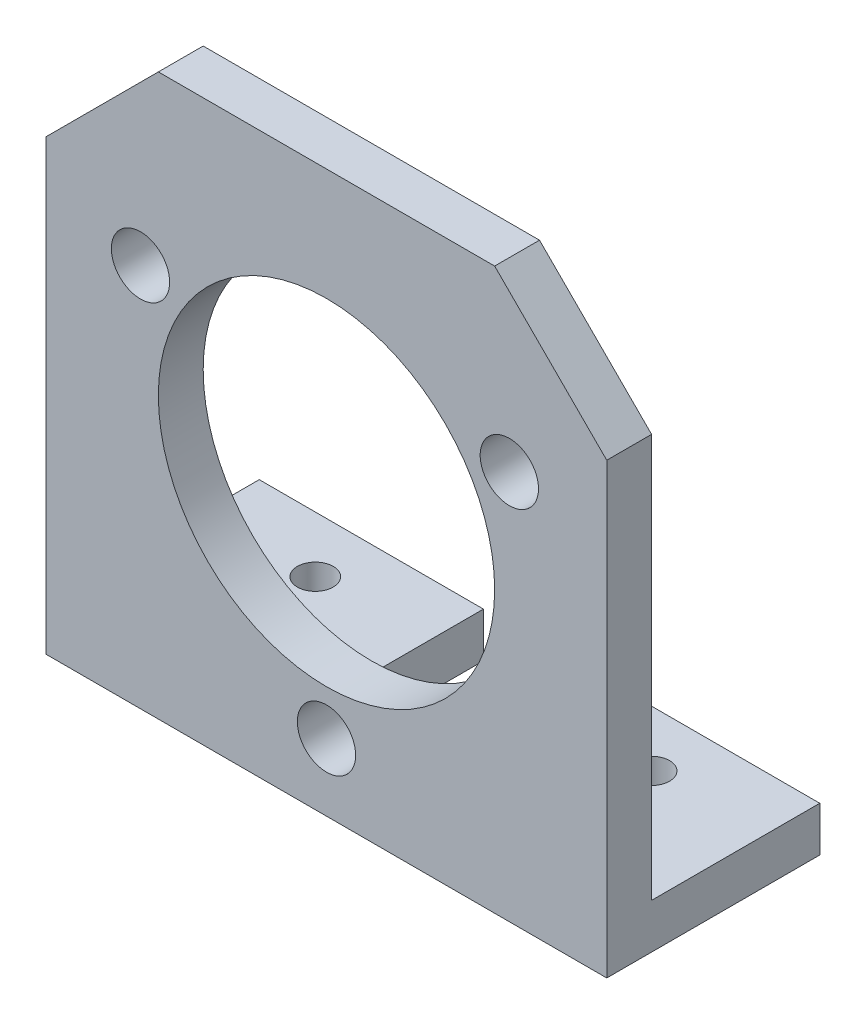
SolidWorks part; units mm, degrees
ref_plane "前视基准面" through (0, 0, 0) normal (0, 0, 1) x (1, 0, 0)
ref_plane "上视基准面" through (0, 0, 0) normal (0, 1, 0) x (1, 0, 0)
ref_plane "右视基准面" through (0, 0, 0) normal (1, 0, 0) x (0, 0, -1)
sketch "草图1" plane through (0, 0, 0) normal (0, 0, 1) x (1, 0, 0)
  line L1 (-25, 0) -> (-25, -25)
  line L2 (25, 0) -> (25, -25)
  line L3 (-25, -25) -> (25, -25)
  line L4 (-25, -21) -> (-5, -21)
  line L5 (5, -21) -> (25, -21)
  line L6 (-5, -21) -> (-5, -25)
  line L7 (5, -21) -> (5, -25)
  line L8 (0, 25) -> (-15, 25)
  line L9 (-25, 15) -> (-25, 0)
  line L10 (-15, 25) -> (-25, 15)
  line L11 (0, 25) -> (15, 25)
  line L12 (25, 15) -> (15, 25)
  line L13 (25, 15) -> (25, 0)
  line L14 (-25, 0) -> (25, 0) construction
  line L15 (0, 28) -> (0, -28) construction
  line L16 (-13.0997, 7.3073) -> (-21.1797, 11.8145) construction
  line L17 (12.8762, 7.6943) -> (20.5365, 12.2718) construction
  circle A0 centre (0, 0) radius 15
  circle A1 centre (-16.593, 9.2559) radius 2.6
  circle A2 centre (16.3099, 9.7462) radius 2.6
  circle A3 centre (0, -19) radius 2.6
  circle A4 centre (0, 0) radius 19 construction
extrude "凸台-拉伸1" add sketch "草图1" along normal blind 4 contours L13 L12 L11 L8 L10 L9 L1 L4 L6 L3 L7 L5 L2 A3 A2 A1 A0 | L5 L7 L3 L2 | L6 L4 L1 L3
sketch "草图3" plane through (0, 0, 0) normal (0, 0, -1) x (-1, 0, 0)
  line L1 (-25, -21) -> (-5, -21)
  line L2 (-25, -21) -> (-25, -25)
  line L3 (-25, -25) -> (-5, -25)
  line L4 (-5, -21) -> (-5, -25)
  line L5 (5, -21) -> (25, -21)
  line L6 (5, -21) -> (5, -25)
  line L7 (5, -25) -> (25, -25)
  line L8 (25, -21) -> (25, -25)
extrude "凸台-拉伸2" add sketch "草图3" along normal blind 15
sketch "草图4" plane through (0, -25, 0) normal (0, -1, 0) x (1, 0, 0)
  line L0 (-15, -10) -> (15, -10) construction
  line L1 (-25, 4) -> (25, 4) construction
  line L2 (-25, 4) -> (-25, -15) construction
  circle A0 centre (-15, -10) radius 1.6
  circle A1 centre (15, -10) radius 1.6
  dimension "D4" = 3.2
  dimension "D1" = 14
  dimension "D2" = 30
  dimension "D3" = 10
extrude "切除-拉伸1" cut sketch "草图4" against normal blind 15
